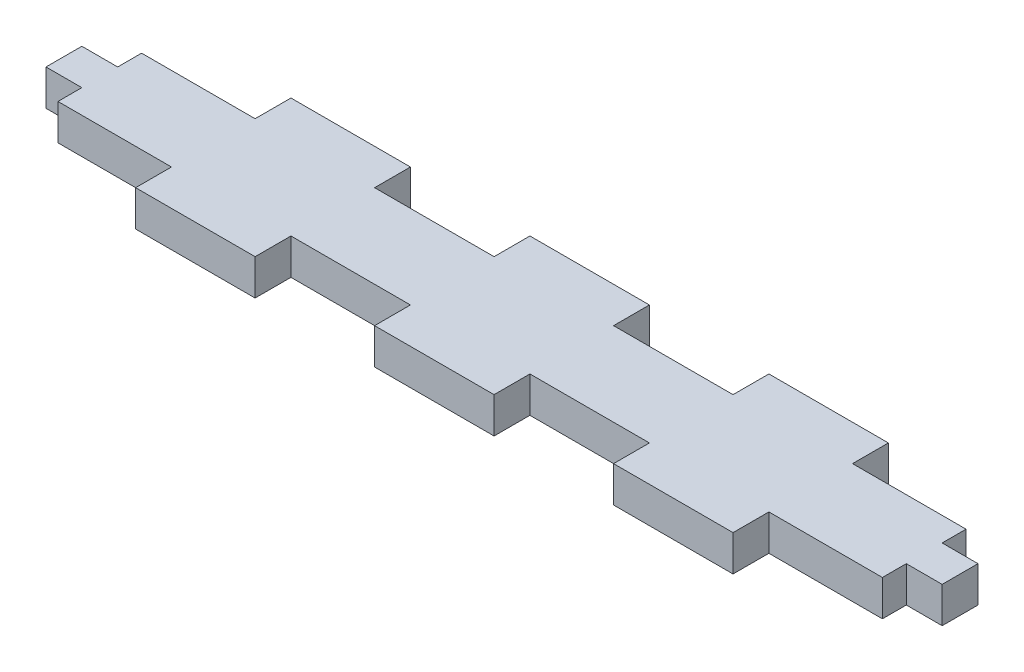
SolidWorks part; units mm, degrees
ref_plane "Alzado" through (0, 0, 0) normal (0, 0, 1) x (1, 0, 0)
ref_plane "Planta" through (0, 0, 0) normal (0, 1, 0) x (1, 0, 0)
ref_plane "Vista lateral" through (0, 0, 0) normal (1, 0, 0) x (0, 0, -1)
sketch "Croquis1" plane through (0, 0, 0) normal (0, 1, 0) x (1, 0, 0)
  line L0 (12.5, 0) -> (22.5, 0)
  line L1 (75, 5) -> (75, 8)
  line L2 (62.5, 13) -> (52.5, 13)
  line L3 (0, 8) -> (0, 5)
  line L4 (0, 6.5) -> (0, 8)
  line L5 (0, 8) -> (3, 8)
  line L6 (3, 8) -> (3, 10)
  line L7 (0, 6.5) -> (0, 5)
  line L8 (0, 5) -> (3, 5)
  line L9 (3, 5) -> (3, 3)
  line L10 (37.5, 13) -> (32.5, 13)
  line L11 (32.5, 13) -> (32.5, 10)
  line L12 (32.5, 10) -> (22.5, 10)
  line L13 (22.5, 10) -> (22.5, 13)
  line L14 (22.5, 13) -> (12.5, 13)
  line L15 (12.5, 13) -> (12.5, 10)
  line L16 (12.5, 10) -> (3, 10)
  line L18 (62.5, 10) -> (72, 10)
  line L19 (62.5, 13) -> (62.5, 10)
  line L20 (52.5, 10) -> (52.5, 13)
  line L21 (42.5, 10) -> (52.5, 10)
  line L22 (42.5, 13) -> (42.5, 10)
  line L23 (72, 5) -> (72, 3)
  line L24 (75, 5) -> (72, 5)
  line L25 (72, 8) -> (72, 10)
  line L26 (75, 8) -> (72, 8)
  line L28 (42.5, 0) -> (42.5, 3)
  line L29 (42.5, 3) -> (52.5, 3)
  line L30 (52.5, 3) -> (52.5, 0)
  line L31 (62.5, 0) -> (62.5, 3)
  line L32 (62.5, 3) -> (72, 3)
  line L33 (12.5, 3) -> (3, 3)
  line L34 (12.5, 0) -> (12.5, 3)
  line L35 (22.5, 3) -> (22.5, 0)
  line L36 (32.5, 3) -> (22.5, 3)
  line L37 (32.5, 0) -> (32.5, 3)
  line L38 (32.5, 0) -> (42.5, 0)
  line L39 (52.5, 0) -> (62.5, 0)
  line L41 (42.5, 13) -> (32.5, 13)
  line L42 (22.5, 13) -> (12.5, 13)
  dimension "D3" = 1.5
  dimension "D4" = 3
  dimension "D6" = 5
  dimension "D7" = 3
  dimension "D8" = 10
  dimension "D9" = 10
extrude "Saliente-Extruir1" add sketch "Croquis1" along normal blind 3 contours L22 L41 L10 L11 L12 L13 L14 L15 L16 L6 L5 L3 L8 L9 L33 L34 L0 L35 L36 L37 L38 L28 L29 L30 L39 L31 L32 L23 L24 L1 L26 L25 L18 L19 L2 L20 L21
